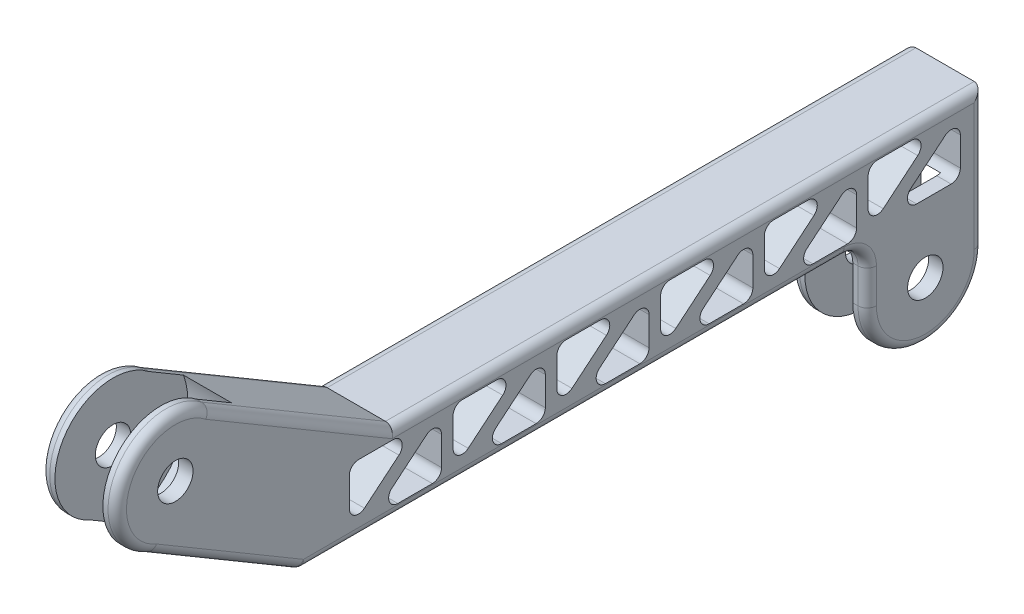
SolidWorks part; units mm, degrees
ref_plane "Front Plane" through (0, 0, 0) normal (0, 0, 1) x (1, 0, 0)
ref_plane "Top Plane" through (0, 0, 0) normal (0, 1, 0) x (1, 0, 0)
ref_plane "Right Plane" through (0, 0, 0) normal (1, 0, 0) x (0, 0, -1)
sketch "Sketch2" plane through (0, 0, 0) normal (1, 0, 0) x (0, 0, -1)
  line L0 (92.075, -10.8204) -> (92.075, -18.7579)
  line L1 (0, 0) -> (92.075, 0)
  line L3 (5.2043, -10.8204) -> (83.068, -10.8204)
  line L4 (92.075, 0) -> (92.075, -10.8204)
  line L5 (76.073, -18.7579) -> (76.073, -13.9954)
  line L6 (-4.9694, -9.0007) -> (-22.3615, 1.2686)
  line L8 (-14.29, 14.9386) -> (7.1812, 2.2608)
  line L9 (-28.7091, 14.2345) -> (-19.1921, 8.6151) construction
  line L10 (84.074, -18.7579) -> (-19.1921, 8.6151) construction
  line L11 (85.08, -10.8204) -> (92.075, -10.8204)
  line L12 (7.1812, 2.2608) -> (11.01, 0)
  line L13 (5.2043, -10.8204) -> (-1.8875, -10.8204)
  line L14 (-4.9694, -9.0007) -> (-1.8875, -10.8204)
  line L15 (-6.5253, -8.082) -> (1.5462, 5.588) construction
  line L16 (-19.1921, 8.6151) -> (-2.4896, -1.247) construction
  circle A0 centre (84.074, -18.7579) radius 2.4384
  circle A1 centre (84.074, -18.7579) radius 8.001
  arc A2 (76.073, -13.9954) -> (72.898, -10.8204) centre (72.898, -13.9954) ccw
  circle A6 centre (-19.1921, 8.6151) radius 2.4384
  circle A7 centre (-19.1921, 8.6151) radius 8.001
  point P30 (-2.4896, -1.247)
  dimension "D3" = 4.8768
  dimension "D6" = 6.35
  dimension "D8" = 20.1977
  dimension "D11" = 24.9347
  dimension "D2" = 15.875
  dimension "D4" = 4.8768
  dimension "D9" = 16.002
  dimension "D1" = 92.075
  dimension "D5" = 7.9375
  dimension "D7" = 149.44
  dimension "D10" = 106.8324
  dimension "D12" = 3.5791
  dimension "D14" = 10.8204
extrude "Boss-Extrude1" add sketch "Sketch2" along normal blind 10.5664
sketch "Sketch3" plane through (0, 0, 0) normal (-1, 0, 0) x (0, 0, 1)
  line L0 (-76.2, -9.3789) -> (-76.2, -1.4414)
  line L1 (-76.2, -1.4414) -> (-85.725, -1.4414)
  line L2 (-85.725, -1.4414) -> (-76.2, -9.3789)
  line L3 (-79.375, -9.3789) -> (-88.9, -1.4414)
  line L4 (-88.9, -1.4414) -> (-88.9, -9.3789)
  line L5 (-88.9, -9.3789) -> (-79.375, -9.3789)
  line L6 (-76.2, -9.3789) -> (-88.9, -9.3789) construction
  line L7 (-72.898, -5.4102) -> (-66.2437, -5.4102) construction
  line L8 (-72.898, -10.8204) -> (-72.898, 0) construction
  line L9 (-11.01, 0) -> (-92.075, 0) construction
  line L10 (-76.2, -5.4102) -> (-73.6653, -5.4102) construction
  line L11 (-92.075, 0) -> (-92.075, -18.7579) construction
  line L12 (-74.6125, -9.3789) -> (-65.0875, -9.3789)
  line L13 (-65.0875, -9.3789) -> (-74.6125, -1.4414)
  line L14 (-74.6125, -1.4414) -> (-74.6125, -9.3789)
  line L15 (-61.9125, -9.3789) -> (-61.9125, -1.4414)
  line L16 (-71.4375, -1.4414) -> (-61.9125, -9.3789)
  line L17 (-61.9125, -1.4414) -> (-71.4375, -1.4414)
  line L18 (-60.325, -9.3789) -> (-50.8, -9.3789)
  line L19 (-50.8, -9.3789) -> (-60.325, -1.4414)
  line L20 (-60.325, -1.4414) -> (-60.325, -9.3789)
  line L21 (-47.625, -9.3789) -> (-47.625, -1.4414)
  line L22 (-57.15, -1.4414) -> (-47.625, -9.3789)
  line L23 (-47.625, -1.4414) -> (-57.15, -1.4414)
  line L24 (-46.0375, -9.3789) -> (-36.5125, -9.3789)
  line L25 (-36.5125, -9.3789) -> (-46.0375, -1.4414)
  line L26 (-46.0375, -1.4414) -> (-46.0375, -9.3789)
  line L27 (-33.3375, -9.3789) -> (-33.3375, -1.4414)
  line L28 (-42.8625, -1.4414) -> (-33.3375, -9.3789)
  line L29 (-33.3375, -1.4414) -> (-42.8625, -1.4414)
  line L30 (-31.75, -9.3789) -> (-22.225, -9.3789)
  line L31 (-22.225, -9.3789) -> (-31.75, -1.4414)
  line L32 (-31.75, -1.4414) -> (-31.75, -9.3789)
  line L33 (-19.05, -9.3789) -> (-19.05, -1.4414)
  line L34 (-28.575, -1.4414) -> (-19.05, -9.3789)
  line L35 (-19.05, -1.4414) -> (-28.575, -1.4414)
  line L36 (-17.4625, -9.3789) -> (-7.9375, -9.3789)
  line L37 (-7.9375, -9.3789) -> (-17.4625, -1.4414)
  line L38 (-17.4625, -1.4414) -> (-17.4625, -9.3789)
  line L39 (-4.7625, -9.3789) -> (-4.7625, -1.4414)
  line L40 (-14.2875, -1.4414) -> (-4.7625, -9.3789)
  line L41 (-4.7625, -1.4414) -> (-14.2875, -1.4414)
  arc A0 (-78.283, -7.6431) -> (-76.2, -6.6674) centre (-77.47, -6.6674) ccw
  arc A1 (-76.2, -2.7114) -> (-77.47, -1.4414) centre (-77.47, -2.7114) ccw
  arc A2 (-82.2172, -1.4414) -> (-83.0302, -3.6871) centre (-82.2172, -2.7114) ccw
  arc A3 (-82.8828, -9.3789) -> (-82.0698, -7.1333) centre (-82.8828, -8.1089) ccw
  arc A4 (-88.9, -8.1089) -> (-87.63, -9.3789) centre (-87.63, -8.1089) ccw
  arc A5 (-86.817, -3.1773) -> (-88.9, -4.153) centre (-87.63, -4.153) ccw
  arc A6 (-74.6125, -8.1089) -> (-73.3425, -9.3789) centre (-73.3425, -8.1089) ccw
  arc A7 (-68.5953, -9.3789) -> (-67.7823, -7.1333) centre (-68.5953, -8.1089) ccw
  arc A8 (-72.5295, -3.1773) -> (-74.6125, -4.153) centre (-73.3425, -4.153) ccw
  arc A9 (-67.9297, -1.4414) -> (-68.7427, -3.6871) centre (-67.9297, -2.7114) ccw
  arc A10 (-61.9125, -2.7114) -> (-63.1825, -1.4414) centre (-63.1825, -2.7114) ccw
  arc A11 (-63.9955, -7.6431) -> (-61.9125, -6.6674) centre (-63.1825, -6.6674) ccw
  arc A12 (-60.325, -8.1089) -> (-59.055, -9.3789) centre (-59.055, -8.1089) ccw
  arc A13 (-54.3078, -9.3789) -> (-53.4948, -7.1333) centre (-54.3078, -8.1089) ccw
  arc A14 (-58.242, -3.1773) -> (-60.325, -4.153) centre (-59.055, -4.153) ccw
  arc A15 (-53.6422, -1.4414) -> (-54.4552, -3.6871) centre (-53.6422, -2.7114) ccw
  arc A16 (-47.625, -2.7114) -> (-48.895, -1.4414) centre (-48.895, -2.7114) ccw
  arc A17 (-49.708, -7.6431) -> (-47.625, -6.6674) centre (-48.895, -6.6674) ccw
  arc A18 (-46.0375, -8.1089) -> (-44.7675, -9.3789) centre (-44.7675, -8.1089) ccw
  arc A19 (-40.0203, -9.3789) -> (-39.2073, -7.1333) centre (-40.0203, -8.1089) ccw
  arc A20 (-43.9545, -3.1773) -> (-46.0375, -4.153) centre (-44.7675, -4.153) ccw
  arc A21 (-39.3547, -1.4414) -> (-40.1677, -3.6871) centre (-39.3547, -2.7114) ccw
  arc A22 (-33.3375, -2.7114) -> (-34.6075, -1.4414) centre (-34.6075, -2.7114) ccw
  arc A23 (-35.4205, -7.6431) -> (-33.3375, -6.6674) centre (-34.6075, -6.6674) ccw
  arc A24 (-31.75, -8.1089) -> (-30.48, -9.3789) centre (-30.48, -8.1089) ccw
  arc A25 (-25.7328, -9.3789) -> (-24.9198, -7.1333) centre (-25.7328, -8.1089) ccw
  arc A26 (-29.667, -3.1773) -> (-31.75, -4.153) centre (-30.48, -4.153) ccw
  arc A27 (-25.0672, -1.4414) -> (-25.8802, -3.6871) centre (-25.0672, -2.7114) ccw
  arc A28 (-19.05, -2.7114) -> (-20.32, -1.4414) centre (-20.32, -2.7114) ccw
  arc A29 (-21.133, -7.6431) -> (-19.05, -6.6674) centre (-20.32, -6.6674) ccw
  arc A30 (-17.4625, -8.1089) -> (-16.1925, -9.3789) centre (-16.1925, -8.1089) ccw
  arc A31 (-11.4453, -9.3789) -> (-10.6323, -7.1333) centre (-11.4453, -8.1089) ccw
  arc A32 (-15.3795, -3.1773) -> (-17.4625, -4.153) centre (-16.1925, -4.153) ccw
  arc A33 (-10.7797, -1.4414) -> (-11.5927, -3.6871) centre (-10.7797, -2.7114) ccw
  arc A34 (-4.7625, -2.7114) -> (-6.0325, -1.4414) centre (-6.0325, -2.7114) ccw
  arc A35 (-6.8455, -7.6431) -> (-4.7625, -6.6674) centre (-6.0325, -6.6674) ccw
  dimension "D5" = 2.54
  dimension "D1" = 3.175
  dimension "D2" = 7.9375
  dimension "D3" = 9.525
  dimension "D4" = 3.175
  dimension "D6" = 6
extrude "Cut-Extrude2" cut sketch "Sketch3" against normal through all contours L40 A35 L39 A34 L41 A33 | L37 A32 L38 A30 L36 A31 | L34 A29 L33 A28 L35 A27 | L31 A26 L32 A24 L30 A25 | L28 A23 L27 A22 L29 A21 | L25 A20 L26 A18 L24 A19 | L22 A17 L21 A16 L23 A15 | L19 A14 L20 A12 L18 A13 | L3 A5 L4 A4 L5 A3 | L1 A2 L2 A0 L0 A1 | L13 A8 L14 A6 L12 A7 | L16 A11 L15 A10 L17 A9
ref_plane "Plane1" through (5.2832, 0, 0) normal (1, 0, 0) x (0, 0, -1)
sketch "Sketch4" plane through (5.2832, 0, 0) normal (1, 0, 0) x (0, 0, -1)
  circle A0 centre (-19.1921, 8.6151) radius 10.3187
  arc A1 (-14.29, 14.9386) -> (-22.3615, 1.2686) centre (-19.1921, 8.6151) ccw construction
  circle A2 centre (84.074, -18.7579) radius 10.3187
  circle A3 centre (84.074, -18.7579) radius 2.4384 construction
  dimension "D1" = 20.6375
extrude "Cut-Extrude3" cut sketch "Sketch4" against normal blind 3.302 and the other way blind 3.302
fillet "Fillet10" radius 1.27 19 edges at (0, -9.3789, -92.075) (0, -26.7589, -84.074) (0, -16.3766, -76.073) (0, -11.7503, -75.1431) (10.5664, -9.3789, -92.075) (10.5664, -11.7503, -75.1431) (10.5664, -16.3766, -76.073) (10.5664, -26.7589, -84.074) (0, -10.8204, -35.5053) (10.5664, -10.8204, -35.5053) (0, 0, -51.5425) (10.5664, 0, -51.5425) (5.2832, -10.8204, 1.8875) (0, 7.4693, 1.64) (10.5664, 7.4693, 1.64) (0, -4.7759, 12.1245) (10.5664, -4.7759, 12.1245) (0, 12.6831, 26.0817) (10.5664, 12.6831, 26.0817)
